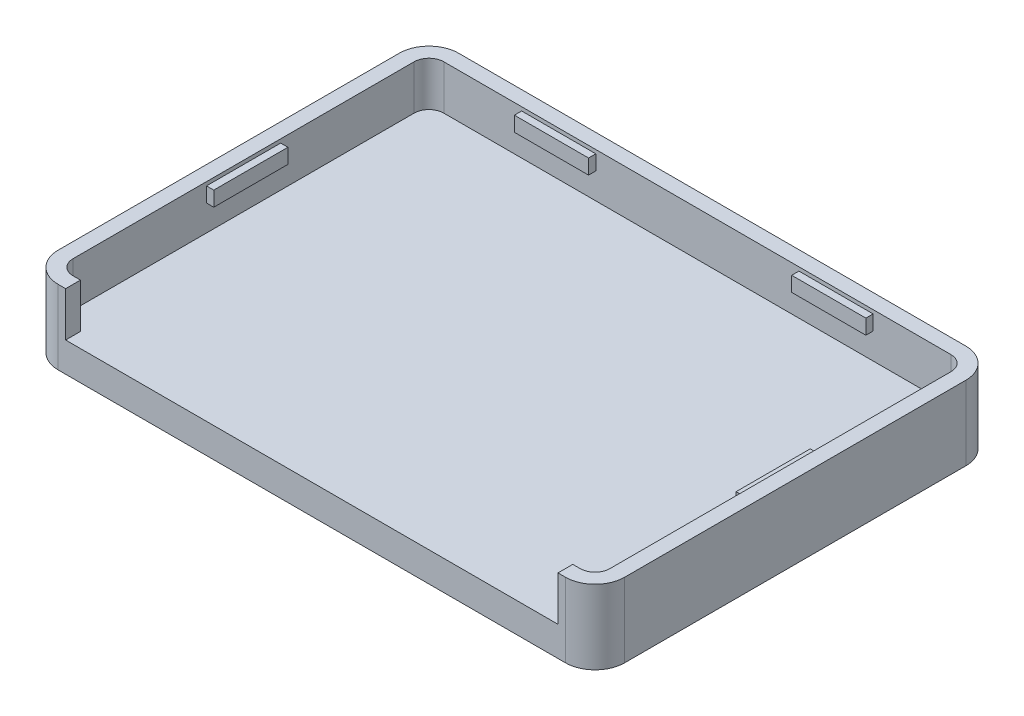
SolidWorks part; units mm, degrees
ref_plane "Plan de face" through (0, 0, 0) normal (0, 0, 1) x (1, 0, 0)
ref_plane "Plan de dessus" through (0, 0, 0) normal (0, 1, 0) x (1, 0, 0)
ref_plane "Plan de droite" through (0, 0, 0) normal (1, 0, 0) x (0, 0, -1)
sketch "Esquisse1" plane through (0, 0, 0) normal (0, 1, 0) x (1, 0, 0)
  line L1 (2, 0) -> (36.2, 0)
  line L2 (0, 2) -> (0, 25)
  line L3 (2, 27) -> (36.2, 27)
  line L4 (38.2, 2) -> (38.2, 25)
  arc A0 (36.2, 0) -> (38.2, 2) centre (36.2, 2) ccw
  arc A1 (36.2, 27) -> (38.2, 25) centre (36.2, 25) cw
  arc A2 (2, 0) -> (0, 2) centre (2, 2) cw
  arc A3 (0, 25) -> (2, 27) centre (2, 25) cw
  point P7 (38.2, 0)
  point P10 (38.2, 27)
  point P13 (0, 0)
  dimension "D3" = 2
  dimension "D1" = 38.2
  dimension "D2" = 27
extrude "Boss.-Extru.1" add sketch "Esquisse1" along normal blind 5
sketch "Esquisse2" plane through (0, 5, 0) normal (0, 1, 0) x (1, 0, 0)
  line L8 (37.2, 2) -> (37.2, 25)
  line L9 (36.2, 26) -> (2, 26)
  line L10 (1, 25) -> (1, 2)
  line L11 (2, 1) -> (36.2, 1)
  line L12 (37.2, 2) -> (37.2, 25)
  line L13 (36.2, 26) -> (2, 26)
  line L14 (1, 25) -> (1, 2)
  line L15 (2, 1) -> (36.2, 1)
  arc A8 (36.2, 1) -> (37.2, 2) centre (36.2, 2) ccw
  arc A9 (37.2, 25) -> (36.2, 26) centre (36.2, 25) ccw
  arc A10 (2, 26) -> (1, 25) centre (2, 25) ccw
  arc A11 (1, 2) -> (2, 1) centre (2, 2) ccw
  arc A12 (36.2, 1) -> (37.2, 2) centre (36.2, 2) ccw
  arc A13 (37.2, 25) -> (36.2, 26) centre (36.2, 25) ccw
  arc A14 (2, 26) -> (1, 25) centre (2, 25) ccw
  arc A15 (1, 2) -> (2, 1) centre (2, 2) ccw
  dimension "D1" = 1
extrude "Enlèv. mat.-Extru.1" cut sketch "Esquisse2" against normal blind 3
sketch "Esquisse3" plane through (0, 0, 0) normal (0, 0, 1) x (1, 0, 0)
  line L0 (2, 5) -> (36.2, 5) construction
  line L1 (2.5, 5) -> (35.7, 5)
  line L2 (2.5, 5) -> (2.5, 2)
  line L3 (2.5, 2) -> (35.7, 2)
  line L4 (35.7, 5) -> (35.7, 2)
  line L5 (2, 5) -> (2, 0) construction
  line L6 (36.2, 5) -> (36.2, 0) construction
  dimension "D1" = 3
  dimension "D2" = 0.5
  dimension "D3" = 0.5
extrude "Enlèv. mat.-Extru.2" cut sketch "Esquisse3" against normal blind 3
sketch "Esquisse4" plane through (1, 0, 0) normal (1, 0, 0) x (0, 0, -1)
  line L0 (25, 5) -> (2, 5) construction
  line L1 (11, 3.75) -> (16, 3.75)
  line L2 (11, 3.75) -> (11, 4.75)
  line L3 (11, 4.75) -> (16, 4.75)
  line L4 (16, 3.75) -> (16, 4.75)
  line L5 (2, 2) -> (2, 5) construction
  point P6 (13.5, 3.75)
  dimension "D1" = 1
  dimension "D2" = 5
  dimension "D3" = 0.25
  dimension "D4" = 11.5
extrude "Boss.-Extru.2" add sketch "Esquisse4" along normal blind 0.489
sketch "Esquisse5" plane through (37.2, 0, 0) normal (-1, 0, 0) x (0, 0, 1)
  line L0 (-2, 5) -> (-25, 5) construction
  line L1 (-16, 4.75) -> (-11, 4.75)
  line L2 (-16, 4.75) -> (-16, 3.75)
  line L3 (-16, 3.75) -> (-11, 3.75)
  line L4 (-11, 4.75) -> (-11, 3.75)
  line L5 (-25, 2) -> (-25, 5) construction
  point P6 (-13.5, 3.75)
  dimension "D1" = 5
  dimension "D2" = 1
  dimension "D3" = 0.25
  dimension "D4" = 11.5
extrude "Boss.-Extru.3" add sketch "Esquisse5" along normal blind 0.489
sketch "Esquisse6" plane through (0, 0, -26) normal (0, 0, 1) x (1, 0, 0)
  line L0 (36.2, 5) -> (2, 5) construction
  line L1 (7.25, 3.75) -> (12.25, 3.75)
  line L2 (7.25, 3.75) -> (7.25, 4.75)
  line L3 (7.25, 4.75) -> (12.25, 4.75)
  line L4 (12.25, 3.75) -> (12.25, 4.75)
  line L5 (2, 2) -> (2, 5) construction
  line L6 (36.2, 2) -> (36.2, 5) construction
  line L7 (30.95, 3.75) -> (25.95, 3.75)
  line L8 (30.95, 3.75) -> (30.95, 4.75)
  line L9 (30.95, 4.75) -> (25.95, 4.75)
  line L10 (25.95, 3.75) -> (25.95, 4.75)
  point P6 (9.75, 3.75)
  point P13 (28.45, 3.75)
  dimension "D1" = 1
  dimension "D2" = 5
  dimension "D3" = 0.25
  dimension "D4" = 7.75
  dimension "D5" = 5
  dimension "D6" = 1
  dimension "D7" = 0.25
  dimension "D8" = 7.75
extrude "Boss.-Extru.4" add sketch "Esquisse6" along normal blind 0.489
